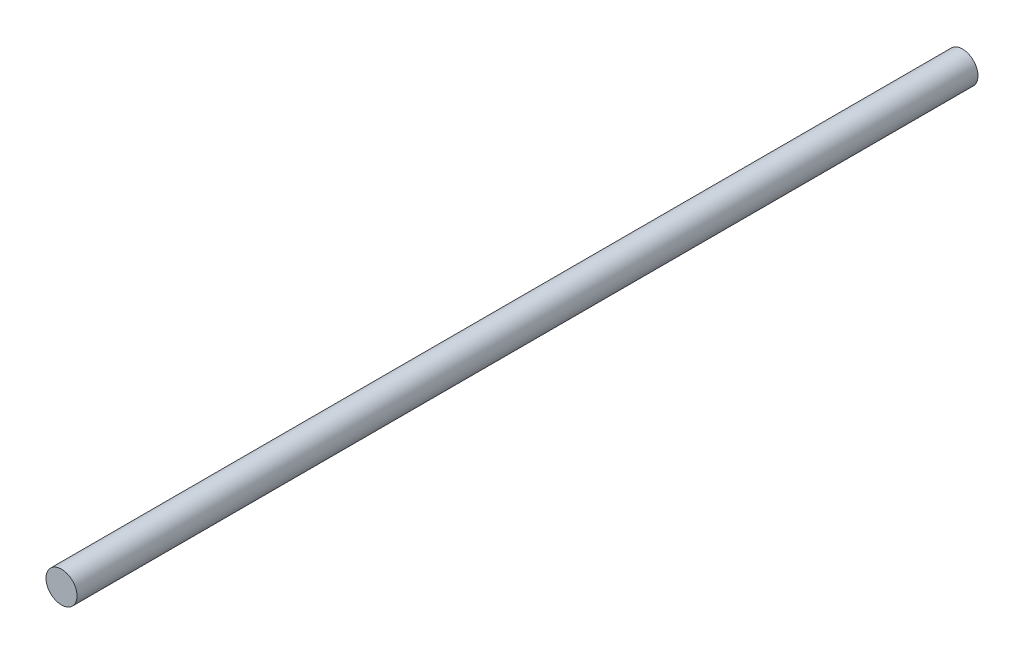
SolidWorks part; units mm, degrees
material "Plain Carbon Steel"
ref_plane "Front Plane" through (0, 0, 0) normal (0, 0, 1) x (1, 0, 0)
ref_plane "Top Plane" through (0, 0, 0) normal (0, 1, 0) x (1, 0, 0)
ref_plane "Right Plane" through (0, 0, 0) normal (1, 0, 0) x (0, 0, -1)
sketch "Sketch1" plane through (0, 0, 0) normal (0, 1, 0) x (1, 0, 0)
  circle A0 centre (0, 0) radius 12.5
  dimension "D1" = 25
extrude "Boss-Extrude1" [suppressed] add sketch "Sketch1" along normal mid plane 500
sketch "Sketch2" [suppressed] plane through (0, 0, 0) normal (0, 0, 1) x (1, 0, 0)
  line L0 (-46.307, 245) -> (67.1241, 245)
  line L1 (12.5, 250) -> (-12.5, 250) construction
  line L2 (-46.307, 245) -> (-46.307, 145)
  line L3 (-46.307, 145) -> (58.77, 145)
  dimension "D1" = 5
  dimension "D2" = 100
split line "Split Line1" [suppressed]
chamfer "Chamfer1" [suppressed] distance 2 angle 45
sketch "Sketch3" [suppressed] plane through (0, -250, 0) normal (0, -1, 0) x (1, 0, 0)
  circle A0 centre (0, 0) radius 12.5
  circle A1 centre (0, 0) radius 10
extrude "Cut-Extrude1" [suppressed] cut sketch "Sketch3" against normal blind 20
sketch "Sketch4" plane through (0, 0, 0) normal (1, 0, 0) x (0, 0, -1)
  line L0 (177.7877, 0) -> (-402.2123, 0)
  point P8 (0, 0)
  dimension "D2" = 580
sketch "Sketch5" plane through (0, 0, 0) normal (0, 0, 1) x (1, 0, 0)
  circle A0 centre (0, 0) radius 12.5
sweep "Sweep3" add path "Sketch4" circular profile diameter 20 parameters "D3"=20
